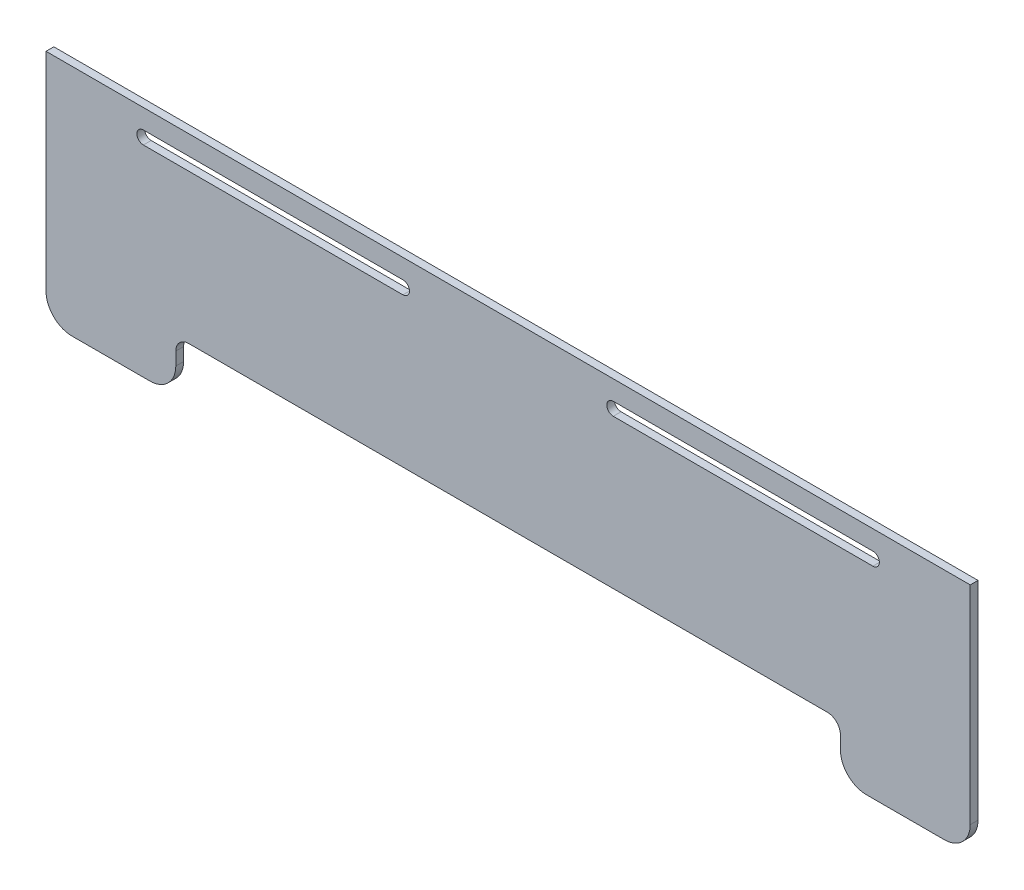
SolidWorks part; units mm, degrees
ref_plane "Front Plane" through (0, 0, 0) normal (0, 0, 1) x (1, 0, 0)
ref_plane "Top Plane" through (0, 0, 0) normal (0, 1, 0) x (1, 0, 0)
ref_plane "Right Plane" through (0, 0, 0) normal (1, 0, 0) x (0, 0, -1)
sketch "Sketch1" plane through (0, 0, 0) normal (0, 0, 1) x (1, 0, 0)
  line L0 (0, -1819.1464) -> (0, 89138.1736) construction
  line L1 (-178, 0) -> (178, 0)
  line L2 (-178, 0) -> (-178, -80)
  line L3 (-123, -70) -> (123, -70)
  line L4 (178, 0) -> (178, -80)
  line L7 (168, -90) -> (138, -90)
  line L8 (128, -75) -> (128, -80)
  line L9 (-128, -75) -> (-128, -80)
  line L10 (-168, -90) -> (-138, -90)
  line L11 (-1125.8735, -20) -> (48874.1265, -20) construction
  line L12 (180, -20) -> (180, 0) construction
  line L13 (-826, -10) -> (49174, -10) construction
  line L14 (40.5, -10) -> (140.5, -10) construction
  line L15 (40.5, -7.5) -> (140.5, -7.5)
  line L16 (40.5, -12.5) -> (140.5, -12.5)
  line L17 (-40.5, -10) -> (-140.5, -10) construction
  line L18 (-40.5, -7.5) -> (-140.5, -7.5)
  line L19 (-40.5, -12.5) -> (-140.5, -12.5)
  arc A0 (128, -75) -> (123, -70) centre (123, -75) ccw
  arc A1 (-128, -75) -> (-123, -70) centre (-123, -75) cw
  arc A2 (178, -80) -> (168, -90) centre (168, -80) cw
  arc A3 (138, -90) -> (128, -80) centre (138, -80) cw
  arc A4 (-138, -90) -> (-128, -80) centre (-138, -80) ccw
  arc A5 (-168, -90) -> (-178, -80) centre (-168, -80) cw
  arc A6 (40.5, -7.5) -> (40.5, -12.5) centre (40.5, -10) ccw
  arc A7 (140.5, -12.5) -> (140.5, -7.5) centre (140.5, -10) ccw
  arc A8 (-40.5, -7.5) -> (-40.5, -12.5) centre (-40.5, -10) cw
  arc A9 (-140.5, -12.5) -> (-140.5, -7.5) centre (-140.5, -10) cw
  point P8 (0, 0)
  point P15 (128, -70)
  point P19 (-128, -70)
  point P22 (178, -90)
  point P25 (128, -90)
  point P28 (-128, -90)
  point P31 (-178, -90)
  point P37 (180, -10)
  point P39 (90.5, -10)
  point P46 (-90.5, -10)
  dimension "D6" = 5
  dimension "D7" = 5
  dimension "D8" = 10
  dimension "D9" = 10
  dimension "D10" = 10
  dimension "D11" = 10
  dimension "D13" = 2.5
  dimension "D1" = 90
  dimension "D2" = 356
  dimension "D3" = 50
  dimension "D4" = 70
  dimension "D5" = 20
  dimension "D12" = 2
  dimension "D14" = 87.5
  dimension "D15" = 100
extrude "Boss-Extrude1" add sketch "Sketch1" along normal blind 3
